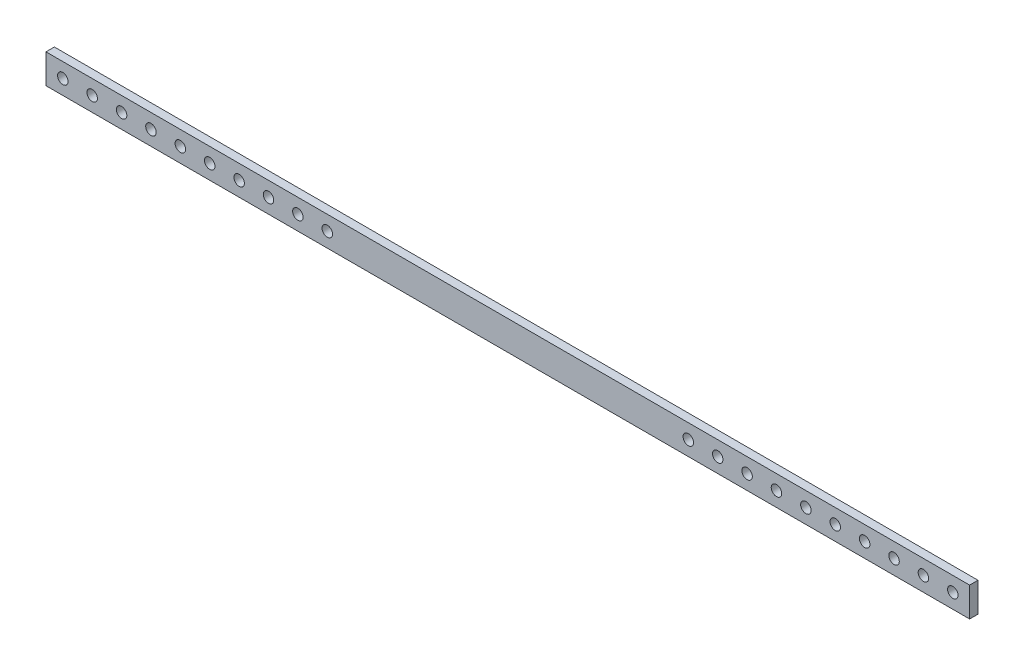
SolidWorks part; units mm, degrees
ref_plane "前视基准面" through (0, 0, 0) normal (0, 0, 1) x (1, 0, 0)
ref_plane "上视基准面" through (0, 0, 0) normal (0, 1, 0) x (1, 0, 0)
ref_plane "右视基准面" through (0, 0, 0) normal (1, 0, 0) x (0, 0, -1)
sketch "草图1" plane through (0, 0, 0) normal (0, 0, 1) x (1, 0, 0)
  line L1 (-110, -3.5) -> (110, -3.5)
  line L2 (-110, -3.5) -> (-110, 3.5)
  line L3 (-110, 3.5) -> (110, 3.5)
  line L4 (110, -3.5) -> (110, 3.5)
  line L5 (-110, -3.5) -> (110, 3.5) construction
  line L6 (-110, 3.5) -> (110, -3.5) construction
  point P0 (0, 0)
  dimension "D1" = 7
  dimension "D2" = 220
extrude "凸台-拉伸1" add sketch "草图1" along normal blind 2
sketch "草图4" plane through (0, 0, 2) normal (0, 0, 1) x (1, 0, 0)
  line L0 (-110, 0) -> (-106, 0) construction
  line L1 (-110, 3.5) -> (-110, -3.5) construction
  dimension "D1" = 4
hole_wizard "M3 螺纹孔2" positions "草图5" profile "草图6" tap size "M3" standard "GB"
sketch "草图5" plane through (0, 0, 2) normal (0, 0, 1) x (1, 0, 0)
  point P0 (-106, 0)
sketch "草图6" plane through (-106, 0, 2) normal (1, 0, 0) x (0, -1, 0)
  line L0 (0, 0) -> (0, 8.2511)
  line L1 (0, 8.2511) -> (1.25, 7.5)
  line L2 (1.25, 7.5) -> (1.25, 0)
  line L5 (1.25, 0) -> (0, 0)
  line L10 (0, 8.2511) -> (-1.25, 7.5) construction
  line L11 (0, -6.35) -> (0, 107.95) construction
  dimension "螺纹孔钻头直径" = 2.5
  dimension "螺纹孔钻头深度" = 7.5
  dimension "导头角度" = 118
cosmetic thread "孔螺蚊线2" parameters "D1"=2, "D2"=3
pattern_linear "阵列(线性)2" count 10 spacing 7 along (1, 0, 0) of "M3 螺纹孔2"
mirror "镜向1" about plane through (0, 0, 0) normal (1, 0, 0) of "阵列(线性)2", "M3 螺纹孔2"
